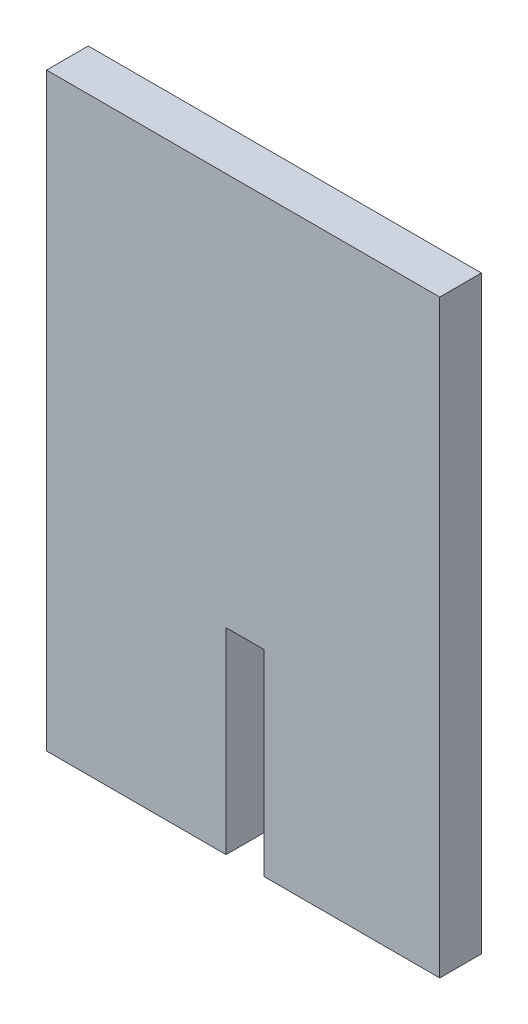
SolidWorks part; units mm, degrees
ref_plane "Front Plane" through (0, 0, 0) normal (0, 0, 1) x (1, 0, 0)
ref_plane "Top Plane" through (0, 0, 0) normal (0, 1, 0) x (1, 0, 0)
ref_plane "Right Plane" through (0, 0, 0) normal (1, 0, 0) x (0, 0, -1)
sketch "Sketch1" plane through (0, 0, 0) normal (0, 0, 1) x (1, 0, 0)
  line L0 (1.3335, -19.05) -> (12.7, -19.05)
  line L1 (-12.7, -19.05) -> (-1.1049, -19.05)
  line L2 (-12.7, -19.05) -> (-12.7, 19.05)
  line L3 (-12.7, 19.05) -> (12.7, 19.05)
  line L4 (12.7, -19.05) -> (12.7, 19.05)
  line L5 (-12.7, -19.05) -> (12.7, 19.05) construction
  line L6 (-12.7, 19.05) -> (12.7, -19.05) construction
  line L8 (-1.1049, -19.05) -> (-1.1049, -6.35)
  line L9 (-1.1049, -6.35) -> (1.3335, -6.35)
  line L10 (1.3335, -19.05) -> (1.3335, -6.35)
  line L11 (0.2286, -19.05) -> (1.3335, -6.35) construction
  line L12 (-1.1049, -6.35) -> (0.2286, -19.05) construction
  point P0 (0, 0)
  point P6 (0.2286, -19.05)
  dimension "D1" = 38.1
  dimension "D2" = 25.4
  dimension "D4" = 2.4384
  dimension "D3" = 12.7
extrude "Boss-Extrude1" add sketch "Sketch1" along normal blind 2.6924
equation "\"T\"= 0.106"
equation "\"D4@Sketch1\"=\"T\"-0.010"
equation "\"D1@Boss-Extrude1\"=\"T\""
